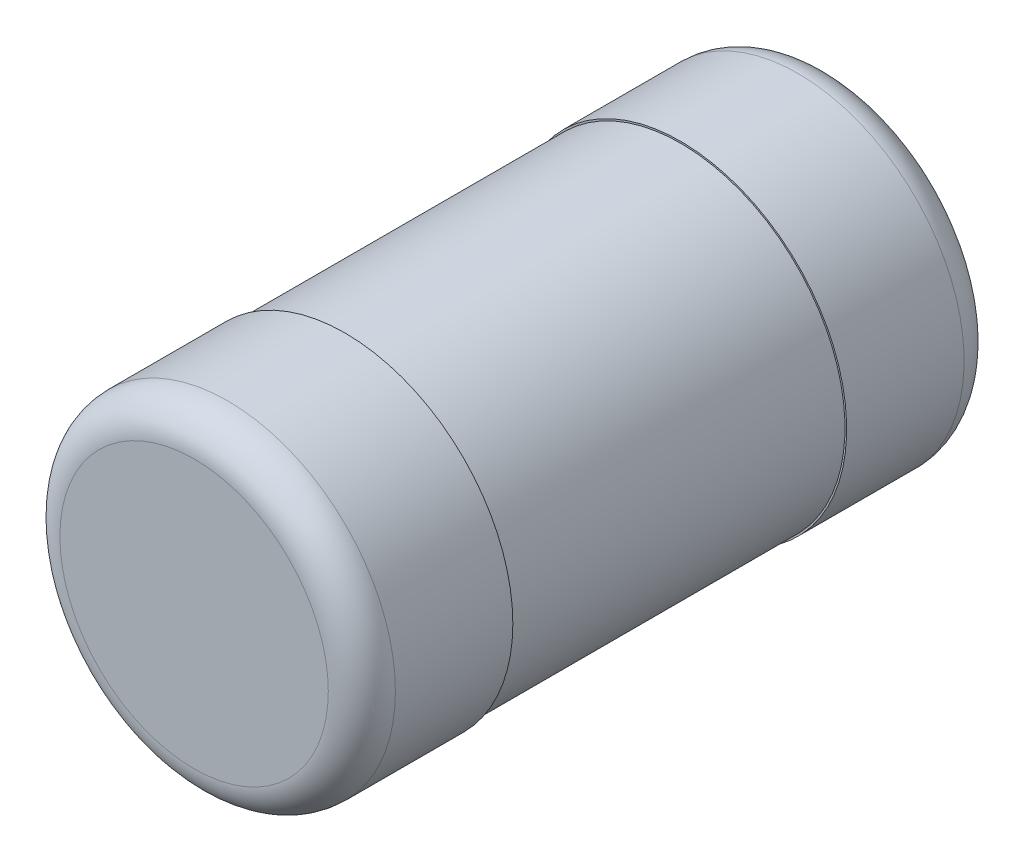
SolidWorks part; units mm, degrees
ref_plane "정면" through (0, 0, 0) normal (0, 0, 1) x (1, 0, 0)
ref_plane "윗면" through (0, 0, 0) normal (0, 1, 0) x (1, 0, 0)
ref_plane "우측면" through (0, 0, 0) normal (1, 0, 0) x (0, 0, -1)
sketch "스케치1" plane through (0, 0, 0) normal (0, 0, 1) x (1, 0, 0)
  circle A0 centre (0, 0) radius 2.45
  dimension "D1" = 4.9
extrude "보스-돌출1" add sketch "스케치1" along normal blind 5
sketch "스케치2" plane through (0, 0, 5) normal (0, 0, 1) x (1, 0, 0)
  circle A0 centre (0, 0) radius 2.5
  dimension "D1" = 5
extrude "보스-돌출2" add sketch "스케치2" along normal blind 2.25
sketch "스케치3" plane through (0, 0, 0) normal (0, 0, -1) x (-1, 0, 0)
  circle A0 centre (0, 0) radius 2.475
  dimension "D1" = 4.95
extrude "보스-돌출3" add sketch "스케치3" along normal blind 2.25
fillet "필렛1" radius 0.5 2 edges at (2.5, 0, 7.25) (-2.475, 0, -2.25)
